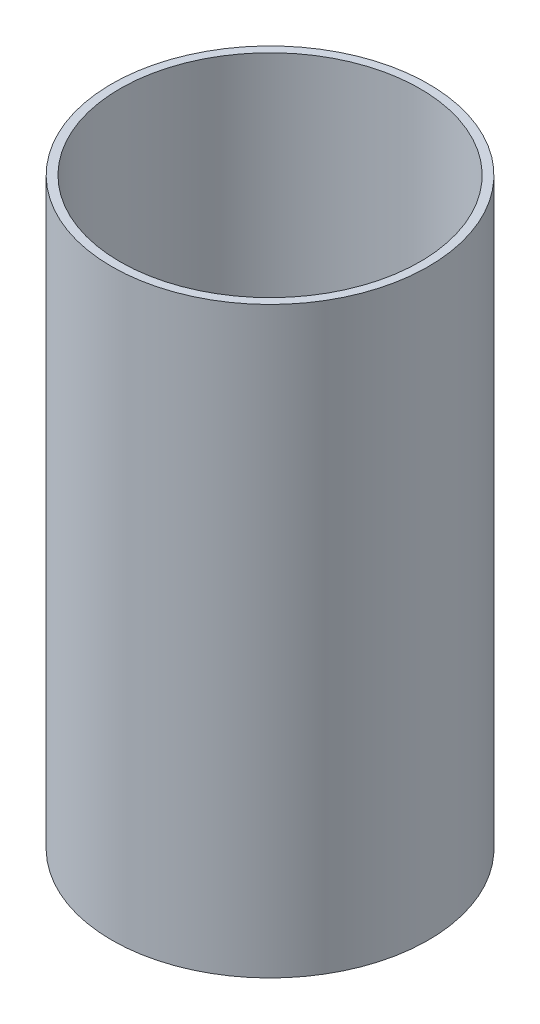
SolidWorks part; units mm, degrees
other "Markup1"
sketch "Sketch3" plane through (-49.53, 177.8, -49.53) normal (-0.149, 0.762, -0.6302) x (-0.1195, 0.6187, 0.7765)
ref_plane "Front Plane" through (0, 0, 0) normal (0, 0, 1) x (1, 0, 0)
ref_plane "Top Plane" through (0, 0, 0) normal (0, 1, 0) x (1, 0, 0)
ref_plane "Right Plane" through (0, 0, 0) normal (1, 0, 0) x (0, 0, -1)
sketch "Sketch2" plane through (0, 0, 0) normal (0, 1, 0) x (1, 0, 0)
  circle A0 centre (0, 0) radius 48.26
  circle A1 centre (0, 0) radius 45.72
  dimension "D1" = 96.52
  dimension "D2" = 2.54
extrude "Boss-Extrude1" add sketch "Sketch2" along normal blind 177.8
